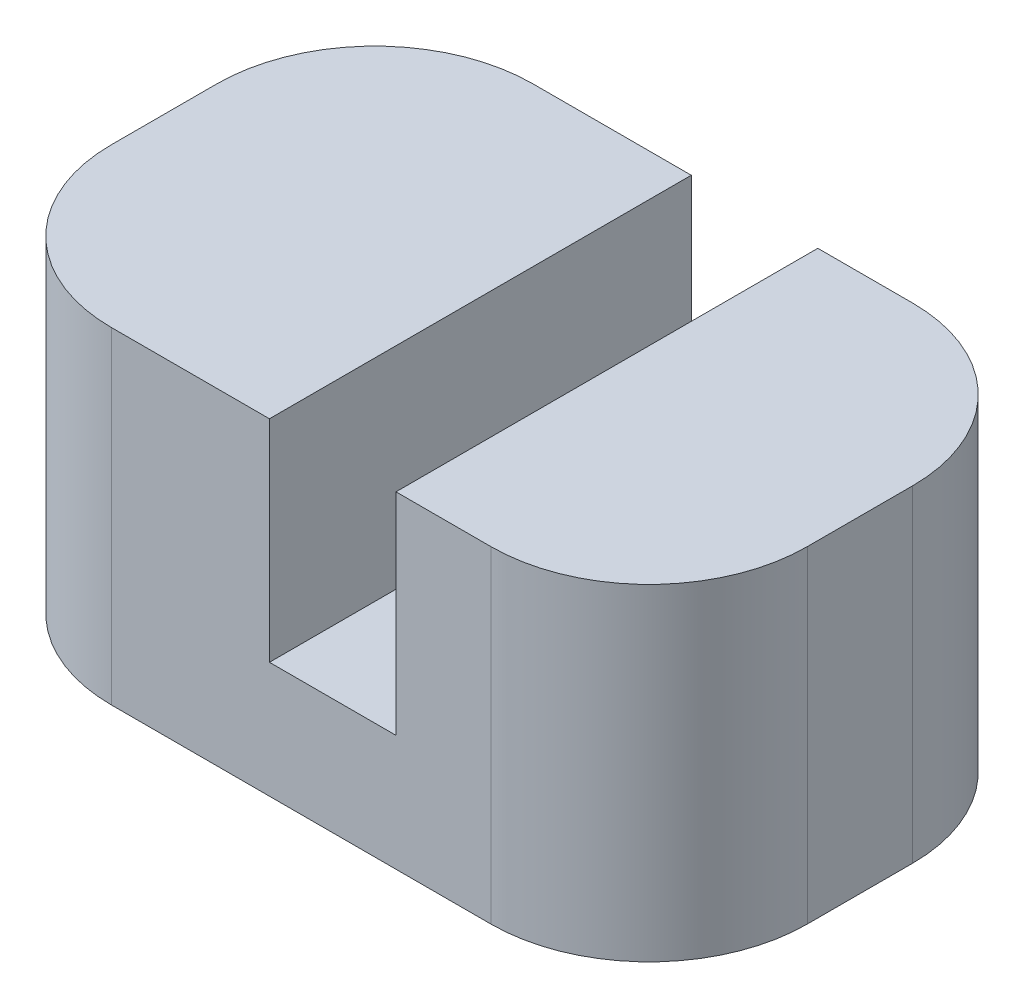
SolidWorks part; units mm, degrees
ref_plane "Alzado" through (0, 0, 0) normal (0, 0, 1) x (1, 0, 0)
ref_plane "Planta" through (0, 0, 0) normal (0, 1, 0) x (1, 0, 0)
ref_plane "Vista lateral" through (0, 0, 0) normal (1, 0, 0) x (0, 0, -1)
sketch "Croquis1" plane through (0, 0, 0) normal (0, 1, 0) x (1, 0, 0)
  line L0 (126.4716, 0) -> (0, 0) construction
  line L1 (15, 10) -> (-18, 10)
  line L2 (15, 10) -> (15, -10)
  line L3 (15, -10) -> (-18, -10)
  line L4 (-18, 10) -> (-18, -10)
  line L5 (0, 0) -> (0, 99.3902) construction
  dimension "D1" = 15
  dimension "D2" = 18
  dimension "D3" = 10
  dimension "D4" = 10
extrude "Saliente-Extruir1" add sketch "Croquis1" along normal blind 15.5
sketch "Croquis2" [suppressed] plane through (0, 15.5, 0) normal (0, 1, 0) x (1, 0, 0)
  line L0 (0, -13.5785) -> (0, 11.5662) construction
  line L1 (17.9678, 0) -> (-18.423, 0) construction
  circle A0 centre (-11.75, 0) radius 2.5
  circle A1 centre (11.75, 0) radius 2.5
  point P5 (-11.75, 0)
  point P6 (11.75, 0)
  dimension "D2" = 5
  dimension "D1" = 23.5
extrude "Cortar-Extruir1" [suppressed] cut sketch "Croquis2" against normal up to next contours A1 | A0
sketch "Croquis6" plane through (0, 15.5, 0) normal (0, 1, 0) x (1, 0, 0)
  line L0 (15, 10) -> (-18, 10) construction
  line L1 (-3, -10) -> (3, -10)
  line L2 (-3, -10) -> (-3, 10)
  line L3 (-3, 10) -> (3, 10)
  line L4 (3, -10) -> (3, 10)
  line L5 (-3, -10) -> (3, 10) construction
  line L6 (-3, 10) -> (3, -10) construction
  point P0 (0, 0)
  dimension "D1" = 6
extrude "Cortar-Extruir2" cut sketch "Croquis6" against normal blind 10
sketch "Croquis7" [suppressed] plane through (0, 15.5, 0) normal (0, 1, 0) x (1, 0, 0)
  line L0 (15, -10) -> (15, 10) construction
  line L1 (-11.75, 2.5) -> (15, 2.5)
  line L2 (-11.75, 2.5) -> (-11.75, -2.5)
  line L3 (-11.75, -2.5) -> (15, -2.5)
  line L4 (15, 2.5) -> (15, -2.5)
  circle A0 centre (-11.75, 0) radius 2.5 construction
extrude "Cortar-Extruir3" [suppressed] cut sketch "Croquis7" against normal up to next
fillet "Redondeo1" radius 7.5 4 edges at (-18, 7.75, -10) (-18, 7.75, 10) (15, 7.75, -10) (15, 7.75, 10)
